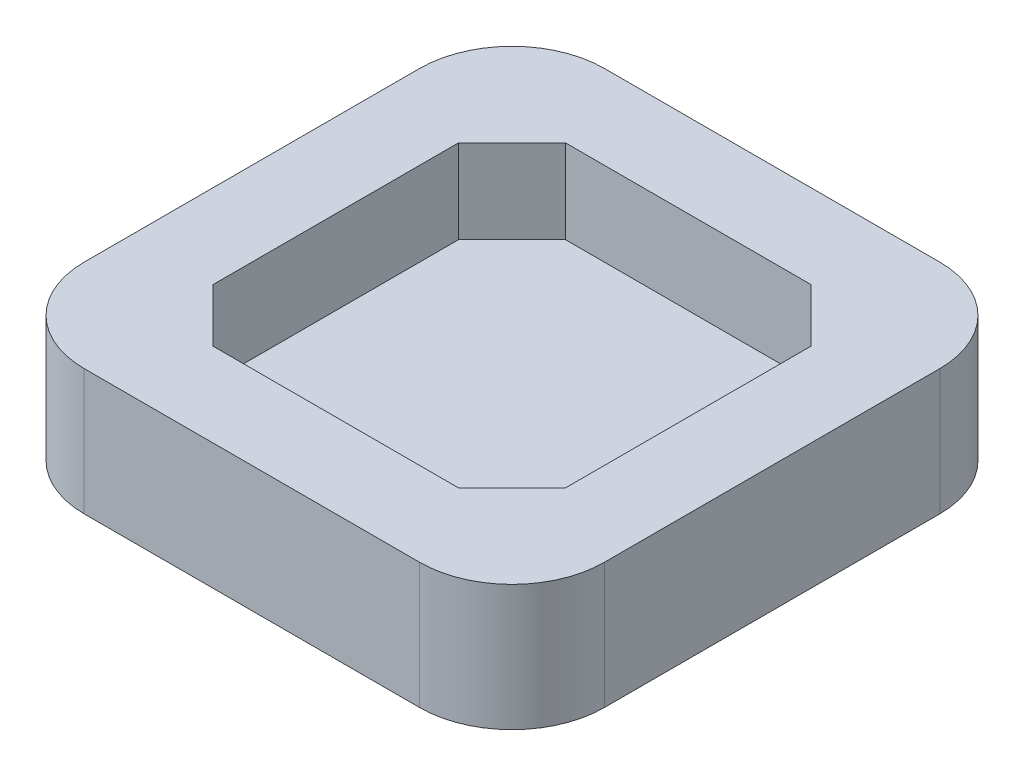
SolidWorks part; units mm, degrees
ref_plane "Front Plane" through (0, 0, 0) normal (0, 0, 1) x (1, 0, 0)
ref_plane "Top Plane" through (0, 0, 0) normal (0, 1, 0) x (1, 0, 0)
ref_plane "Right Plane" through (0, 0, 0) normal (1, 0, 0) x (0, 0, -1)
sketch "Sketch1" plane through (0, 0, 0) normal (0, 1, 0) x (1, 0, 0)
  line L0 (21, -14.636) -> (14.636, -21)
  line L1 (-21, 21) -> (21, 21)
  line L2 (-21, 21) -> (-21, -21)
  line L3 (-21, -21) -> (21, -21)
  line L4 (21, 21) -> (21, -21)
  line L5 (-14.636, -21) -> (-21, -14.636)
  line L6 (-21, 14.636) -> (-14.636, 21)
  line L7 (14.636, 21) -> (21, 14.636)
  line L9 (-31, -31) -> (31, -31)
  line L10 (-31, -31) -> (-31, 31)
  line L11 (-31, 31) -> (31, 31)
  line L12 (31, -31) -> (31, 31)
  point P10 (17.818, -17.818)
  point P16 (0.4145, -0.3741)
  point P22 (0, 0)
  dimension "D1" = 42
  dimension "D2" = 42
  dimension "D3" = 135
  dimension "D4" = 4.5
  dimension "D5" = 21
  dimension "D6" = 21
  dimension "D8" = 10
  dimension "D9" = 10
  dimension "D10" = 10
  dimension "D11" = 10
  dimension "D7" = 4
extrude "Boss-Extrude1" add sketch "Sketch1" along normal blind 10
sketch "Sketch2" plane through (0, 0, 0) normal (0, -1, 0) x (-1, 0, 0)
  line L1 (-31, 31) -> (31, 31)
  line L2 (-31, 31) -> (-31, -31)
  line L3 (-31, -31) -> (31, -31)
  line L4 (31, 31) -> (31, -31)
extrude "Boss-Extrude2" add sketch "Sketch2" along normal blind 5
fillet "Fillet1" radius 11 4 edges at (-31, 2.5, -31) (-31, 2.5, 31) (31, 2.5, 31) (31, 2.5, -31)
